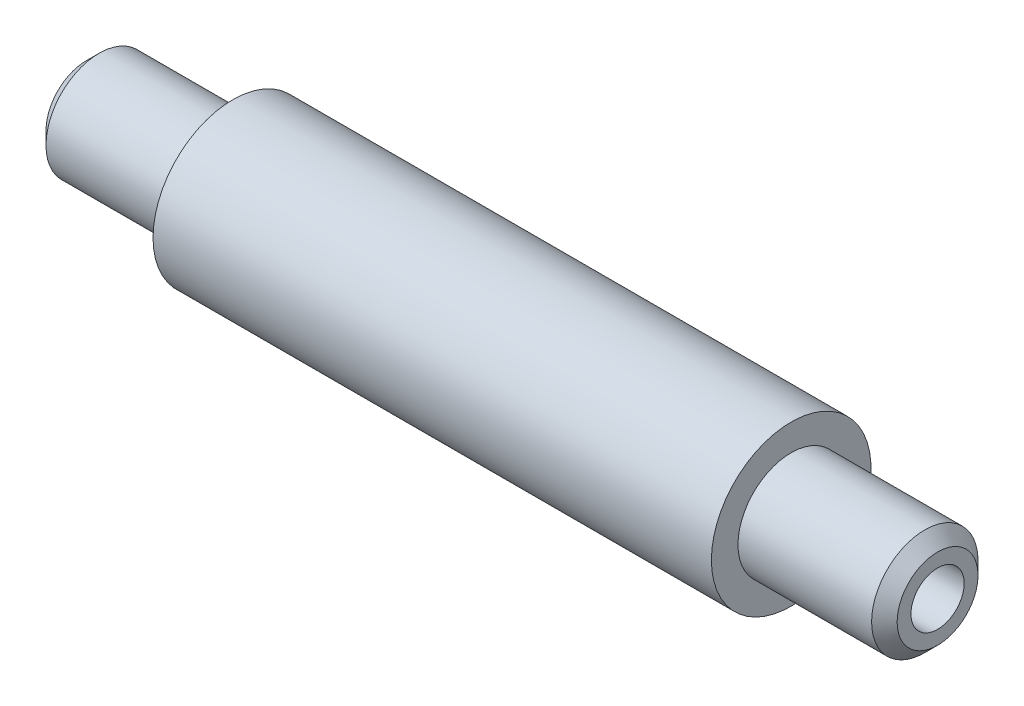
SolidWorks part; units mm, degrees
material "AISI 1020 Steel, Cold Rolled"
ref_plane "Front Plane" through (0, 0, 0) normal (0, 0, 1) x (1, 0, 0)
ref_plane "Top Plane" through (0, 0, 0) normal (0, 1, 0) x (1, 0, 0)
ref_plane "Right Plane" through (0, 0, 0) normal (1, 0, 0) x (0, 0, -1)
sketch "Sketch2" plane through (0, 0, 0) normal (0, 0, 1) x (1, 0, 0)
  line L0 (-50.6869, 0) -> (59.9644, 0) construction
  line L1 (-50.8, 3.175) -> (50.8, 3.175)
  line L2 (50.8, 3.175) -> (50.8, 4.826)
  line L3 (50.8, 4.826) -> (49.276, 6.35)
  line L4 (49.276, 6.35) -> (33.3248, 6.35)
  line L5 (33.3248, 6.35) -> (33.3248, 9.525)
  line L6 (33.3248, 9.525) -> (-33.3248, 9.525)
  line L7 (-33.3248, 9.525) -> (-33.3248, 6.35)
  line L8 (-33.3248, 6.35) -> (-49.276, 6.35)
  line L9 (-49.276, 6.35) -> (-50.8, 4.826)
  line L10 (-50.8, 4.826) -> (-50.8, 3.175)
  point P5 (0, 3.175)
  point P14 (0, 9.525)
  point P15 (-50.8, 6.35)
  point P16 (-41.0532, 10.5584)
  point P17 (-48.4805, 7.4814)
  point P18 (50.8, 5.2532)
  point P19 (-48.6447, 6.8747)
  point P20 (0, 0)
  point P21 (0, 0)
  point P22 (-49.3731, 8.359)
  point P23 (-50.8, 7.347)
  dimension "D1" = 101.6
  dimension "D2" = 17.4752
  dimension "D3" = 12.7
  dimension "D4" = 6.35
  dimension "D5" = 45
  dimension "D6" = 1.524
  dimension "D7" = 45
  dimension "D8" = 19.05
revolve "Revolve1" add sketch "Sketch2" angle 360 about L0
